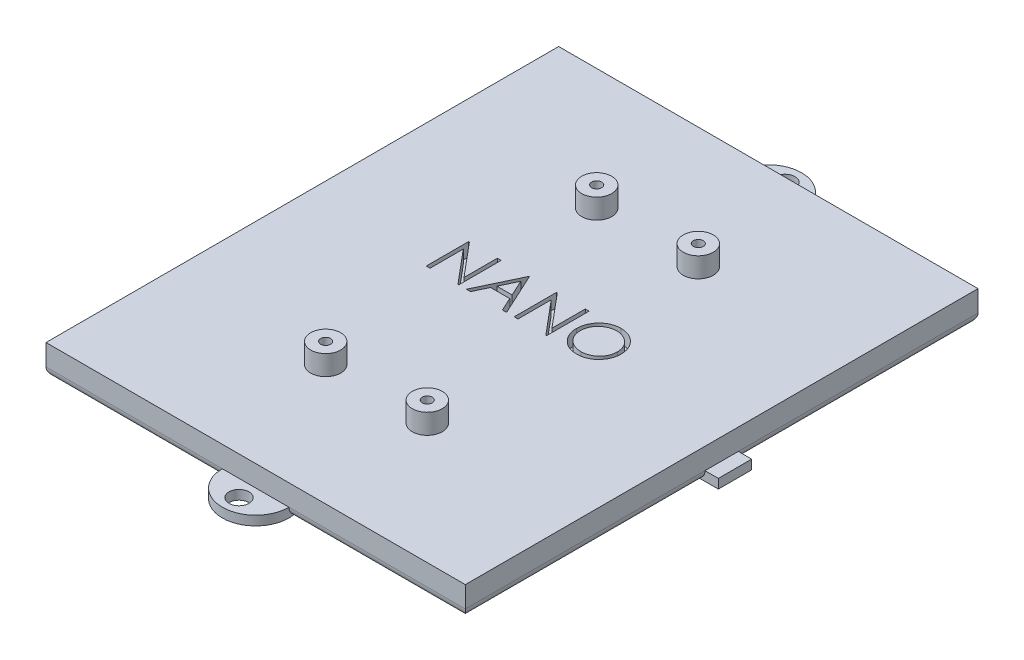
SolidWorks part; units mm, degrees
ref_plane "Front Plane" through (0, 0, 0) normal (0, 0, 1) x (1, 0, 0)
ref_plane "Top Plane" through (0, 0, 0) normal (0, 1, 0) x (1, 0, 0)
ref_plane "Right Plane" through (0, 0, 0) normal (1, 0, 0) x (0, 0, -1)
sketch "Sketch1" plane through (0, 0, 0) normal (0, 1, 0) x (1, 0, 0)
  line L0 (-31.45, 38.45) -> (31.45, 38.45)
  line L5 (-31.45, 38.45) -> (-31.45, -38.45)
  line L6 (-31.45, -38.45) -> (31.45, -38.45)
  line L7 (31.45, 38.45) -> (31.45, -38.45)
  point P11 (-31.45, 0)
  point P12 (0, -38.45)
  dimension "D3" = 76.9
  dimension "D4" = 62.9
extrude "Boss-Extrude1" add sketch "Sketch1" along normal blind 4.575
sketch "Sketch4" plane through (0, 0, 0) normal (0, 1, 0) x (1, 0, 0)
  line L0 (-5, -38.45) -> (5, -38.45)
  line L2 (-31.45, -38.45) -> (31.45, -38.45) construction
  line L4 (0, -38.45) -> (0, -43.45) construction
  arc A0 (-5, -38.45) -> (5, -38.45) centre (0, -38.45) ccw
  circle A2 centre (0, -40.95) radius 1.5
  dimension "D2" = 3
  dimension "D3" = 5
extrude "Boss-Extrude3" add sketch "Sketch4" along normal blind 1.4
sketch "Sketch6" plane through (-31.45, 0, 0) normal (-1, 0, 0) x (0, 0, 1)
  line L0 (-38.45, 0) -> (38.45, 0) construction
  line L1 (-2.5, 0) -> (2.5, 0)
  line L2 (-2.5, 0) -> (-2.5, 1.4)
  line L3 (-2.5, 1.4) -> (2.5, 1.4)
  line L4 (2.5, 0) -> (2.5, 1.4)
  line L5 (43.45, 1.4) -> (38.45, 1.4) construction
  point P6 (0, 1.4)
  point P7 (0, 0)
  dimension "D1" = 5
extrude "Boss-Extrude4" add sketch "Sketch6" along normal blind 2
mirror "Mirror2" about plane through (0, 0, 0) normal (1, 0, 0) of "Boss-Extrude4"
mirror "Mirror1" about plane through (0, 0, 0) normal (0, 0, 1) of "Boss-Extrude3"
fillet "Fillet1" radius 1.4 8 edges at (-18.225, 0, 38.45) (18.225, 0, 38.45) (31.45, 0, -20.475) (31.45, 0, 20.475) (18.225, 0, -38.45) (-18.225, 0, -38.45) (-31.45, 0, 20.475) (-31.45, 0, -20.475)
sketch "Sketch2" plane through (0, 4.575, 0) normal (0, 1, 0) x (1, 0, 0)
  line L1 (-7.6205, 20.3255) -> (7.6205, 20.3255) construction
  line L2 (7.6205, 20.3255) -> (7.6205, -20.3255) construction
  line L3 (7.6205, -20.3255) -> (-7.6205, -20.3255) construction
  line L4 (-7.6205, -20.3255) -> (-7.6205, 20.3255) construction
  circle A8 centre (-7.6205, 20.3255) radius 0.75
  circle A9 centre (7.6205, 20.3255) radius 0.75
  circle A10 centre (-7.6205, -20.3255) radius 0.75
  circle A11 centre (7.6205, -20.3255) radius 0.75
  circle A12 centre (-7.6205, -20.3255) radius 2.25
  circle A13 centre (7.6205, -20.3255) radius 2.25
  circle A14 centre (7.6205, 20.3255) radius 2.25
  circle A15 centre (-7.6205, 20.3255) radius 2.25
  point P8 (7.6205, 0)
  point P9 (0, 20.3255)
  dimension "D1" = 1.5
  dimension "D4" = 1.5
  dimension "D2" = 40.651
  dimension "D3" = 15.241
extrude "Boss-Extrude2" add sketch "Sketch2" along normal blind 3
sketch "Sketch3" plane through (0, 4.575, 0) normal (0, 1, 0) x (1, 0, 0)
  circle A0 centre (7.6205, -20.3255) radius 0.75
  circle A1 centre (-7.6205, -20.3255) radius 0.75
  circle A2 centre (-7.6205, 20.3255) radius 0.75
  circle A3 centre (7.6205, 20.3255) radius 0.75
  circle A6 centre (-7.6205, -20.3255) radius 0.75 construction
extrude "Cut-Extrude1" cut sketch "Sketch3" against normal offset from surface (3.575 mm away) 1 up to face at (0, 0, 0)
sketch "Sketch5" plane through (0, 4.575, 0) normal (0, 1, 0) x (1, 0, 0)
  line L0 (-15, 0) -> (15, 0) construction
  text T0 "NANO\r\n" font "Century Gothic" height in points 24
  point P6 (0, 0)
  dimension "D1" = 30
extrude "Letters" cut sketch "Sketch5" against normal blind 2
